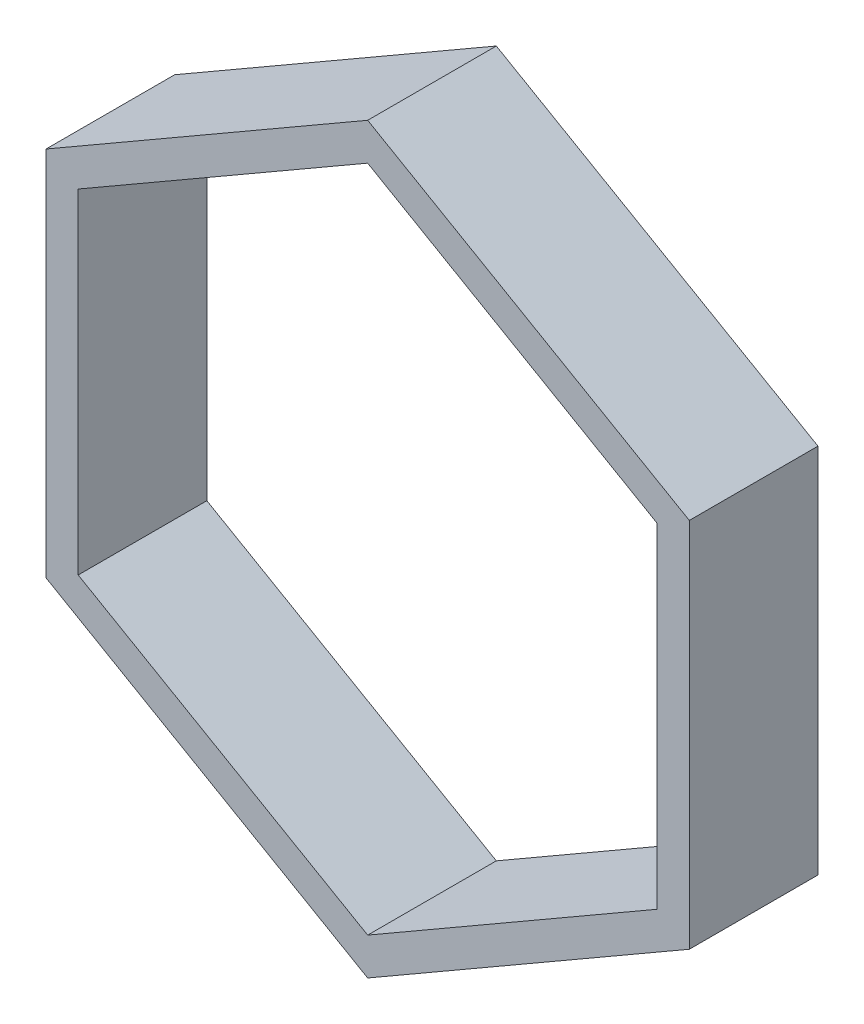
SolidWorks part; units mm, degrees
ref_plane "Front Plane" through (0, 0, 0) normal (0, 0, 1) x (1, 0, 0)
ref_plane "Top Plane" through (0, 0, 0) normal (0, 1, 0) x (1, 0, 0)
ref_plane "Right Plane" through (0, 0, 0) normal (1, 0, 0) x (0, 0, -1)
sketch "Sketch1" plane through (0, 0, 0) normal (0, 0, 1) x (1, 0, 0)
  line L0 (0, 27.588) -> (0, -22.7247) construction
  line L1 (-24.8469, 0) -> (22.1942, 0) construction
  line L2 (0, 10.3923) -> (-9, 5.1962)
  line L3 (0, 11.547) -> (-10, 5.7735)
  line L4 (-10, 5.7735) -> (-10, -5.7735)
  line L5 (-10, -5.7735) -> (0, -11.547)
  line L6 (0, -11.547) -> (10, -5.7735)
  line L7 (10, -5.7735) -> (10, 5.7735)
  line L8 (10, 5.7735) -> (0, 11.547)
  line L9 (-9, 5.1962) -> (-9, -5.1962)
  line L10 (-9, -5.1962) -> (0, -10.3923)
  line L11 (0, -10.3923) -> (9, -5.1962)
  line L12 (9, -5.1962) -> (9, 5.1962)
  line L13 (9, 5.1962) -> (0, 10.3923)
  circle A0 centre (0, 0) radius 10 construction
  dimension "D1" = 20
  dimension "D3" = 18
  dimension "D2" = 1
extrude "Boss-Extrude1" add sketch "Sketch1" along normal blind 4
